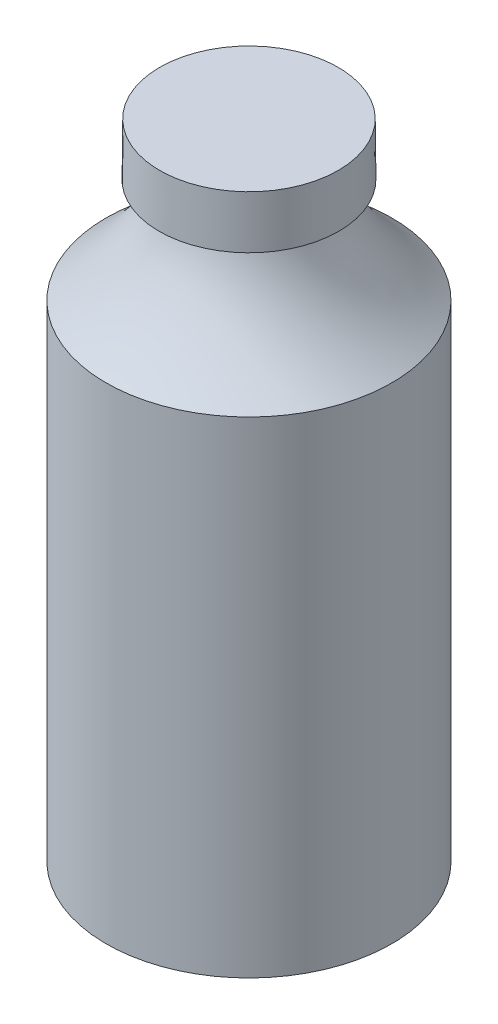
SolidWorks part; units mm, degrees
ref_plane "Front Plane" through (0, 0, 0) normal (0, 0, 1) x (1, 0, 0)
ref_plane "Top Plane" through (0, 0, 0) normal (0, 1, 0) x (1, 0, 0)
ref_plane "Right Plane" through (0, 0, 0) normal (1, 0, 0) x (0, 0, -1)
sketch "Sketch1" plane through (0, 0, 0) normal (0, 0, 1) x (1, 0, 0)
  line L0 (-6.1641, 117.2059) -> (-6.1641, -111.3941)
  line L1 (-6.1641, -111.3941) -> (-56.9641, -111.3941)
  line L2 (-6.1641, 117.2059) -> (-31.5641, 117.2059)
  line L3 (-56.9641, -111.3941) -> (-56.9641, 61.3259)
  spline S0 degree 2 poles (-56.9641, 61.3259) (-26.3561, 85.7288) (-31.5641, 117.2059) knots 0 0 0 1 1 1
  dimension "D1" = 228.6
  dimension "D2" = 50.8
  dimension "D3" = 25.4
  dimension "D4" = 172.72
revolve "Revolve1" add sketch "Sketch1" angle 360 about L0
sketch "Sketch2" plane through (0, 0, 0) normal (0, 0, 1) x (1, 0, 0)
  line L0 (-31.7423, 98.5445) -> (-38.0923, 98.5445)
  line L1 (-31.5641, 117.2059) -> (-37.9141, 117.2059)
  line L2 (-38.0923, 98.5445) -> (-37.9141, 117.2059)
  line L4 (-6.1641, -111.3941) -> (-6.1641, 117.2059)
  line L5 (-56.9641, -111.3941) -> (-6.1641, -111.3941)
  line L6 (-56.9641, 61.3259) -> (-56.9641, -111.3941)
  line L7 (-6.1641, 117.2059) -> (-31.5641, 117.2059)
  line L8 (-6.1641, -111.3941) -> (-6.1641, 117.2059)
  line L9 (-56.9641, -111.3941) -> (-6.1641, -111.3941)
  line L10 (-56.9641, 61.3259) -> (-56.9641, -111.3941)
  line L11 (-6.1641, 117.2059) -> (-31.5641, 117.2059)
  parabola Q1 (-31.5641, 117.2059) -> (-56.9641, 61.3259) focus (-55.7202, 103.2805) apex (-31.7423, 98.5445)
  parabola Q2 (-31.5641, 117.2059) -> (-56.9641, 61.3259) focus (-55.7202, 103.2805) apex (-31.7423, 98.5445)
  dimension "D2" = 6.35
  dimension "D3" = 6.35
  dimension "D1" = 0
revolve "Revolve2" add sketch "Sketch2" angle 360 about L8
sketch "Sketch3" plane through (0, 0, 0) normal (0, 0, 1) x (1, 0, 0)
  line L0 (-31.7423, 98.5445) -> (-38.0923, 98.5445) construction
  line L1 (-38.0923, 98.5445) -> (-37.9141, 117.2059) construction
  line L2 (-31.5641, 117.2059) -> (-37.9141, 117.2059) construction
  line L3 (-6.1641, 117.2059) -> (-31.5641, 117.2059) construction
  line L4 (-6.1641, -111.3941) -> (-6.1641, 117.2059) construction
  line L5 (-56.9641, -111.3941) -> (-6.1641, -111.3941) construction
  line L6 (-56.9641, 61.3259) -> (-56.9641, -111.3941) construction
  line L7 (-31.7423, 98.5445) -> (-38.0923, 98.5445)
  line L8 (-38.0923, 98.5445) -> (-37.9141, 117.2059)
  line L9 (-31.5641, 117.2059) -> (-37.9141, 117.2059)
  line L10 (-6.1641, 117.2059) -> (-31.5641, 117.2059)
  line L11 (-6.1641, -111.3941) -> (-6.1641, 117.2059)
  line L12 (-56.9641, -111.3941) -> (-6.1641, -111.3941)
  line L13 (-56.9641, 61.3259) -> (-56.9641, -111.3941)
  parabola Q0 (-31.5641, 117.2059) -> (-56.9641, 61.3259) focus (-55.7202, 103.2805) apex (-31.7423, 98.5445) construction
  parabola Q1 (-31.5641, 117.2059) -> (-56.9641, 61.3259) focus (-55.7202, 103.2805) apex (-31.7423, 98.5445)
